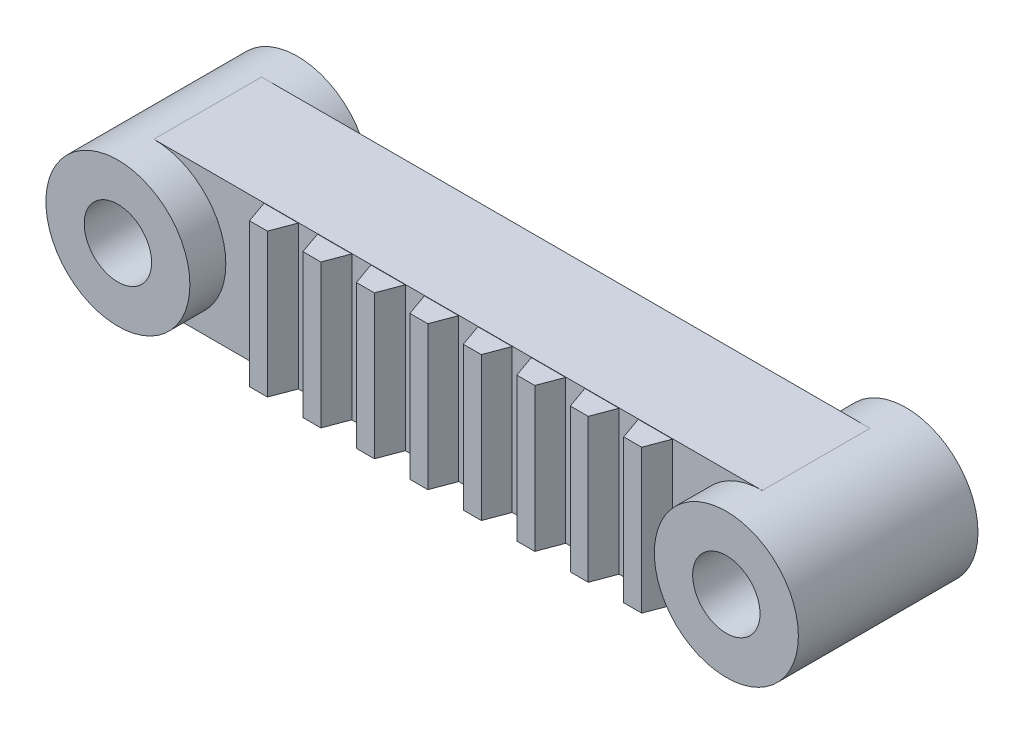
SolidWorks part; units mm, degrees
material "Galvanized Steel"
ref_plane "Front Plane" through (0, 0, 0) normal (0, 0, 1) x (1, 0, 0)
ref_plane "Top Plane" through (0, 0, 0) normal (0, 1, 0) x (1, 0, 0)
ref_plane "Right Plane" through (0, 0, 0) normal (1, 0, 0) x (0, 0, -1)
sketch "Sketch3" plane through (0, 0, 0) normal (0, 0, 1) x (1, 0, 0)
  line L0 (-140288.9448, 14884.8898) -> (-72550.8644, 14884.8898)
  line L1 (-140288.9448, -1150.8743) -> (-72550.8644, -1150.8743)
  circle A2 centre (-140288.9448, 6867.0078) radius 8017.8821
  circle A3 centre (-72550.8644, 6867.0078) radius 8017.8821
  circle A4 centre (-140288.9448, 6867.0078) radius 3750
  circle A5 centre (-72550.8644, 6867.0078) radius 3750
extrude "Boss-Extrude1" add sketch "Sketch3" along normal blind 20000 contours A5 | A3 | A2 | A4
sketch "Sketch4" plane through (0, 0, 0) normal (0, 0, 1) x (1, 0, 0)
  line L0 (-72550.8644, 14884.8898) -> (-140288.9448, 14884.8898)
  line L1 (-72550.8644, -1150.8743) -> (-140288.9448, -1150.8743)
  arc A0 (-72550.8644, 14884.8898) -> (-72550.8644, -1150.8743) centre (-72550.8644, 6867.0078) ccw
  arc A1 (-72550.8644, 14884.8898) -> (-72550.8644, -1150.8743) centre (-72550.8644, 6867.0078) ccw
  arc A2 (-72550.8644, 14884.8898) -> (-72550.8644, -1150.8743) centre (-72550.8644, 6867.0078) ccw
  arc A3 (-140288.9448, 14884.8898) -> (-140288.9448, -1150.8743) centre (-140288.9448, 6867.0078) cw
extrude "Boss-Extrude2" add sketch "Sketch4" along normal blind 12000 from offset 4000 contours L0 A3 L1 A0
sketch "Sketch6" plane through (0, -1150.8743, 0) normal (0, -1, 0) x (1, 0, 0)
  line L0 (-86353.0627, 16000) -> (-85472.8775, 18500)
  line L1 (-72550.8644, 16000) -> (-140288.9448, 16000) construction
  line L2 (-85472.8775, 18500) -> (-83472.8775, 18500)
  line L3 (-83472.8775, 18500) -> (-82532.9823, 16000)
  line L4 (-82532.9823, 16000) -> (-86353.0627, 16000)
  line L7 (-64532.9823, 0) -> (-64532.9823, 20000) construction
  line L10 (-92305.4703, 16000) -> (-91425.2851, 18500)
  line L11 (-91425.2851, 18500) -> (-89425.2851, 18500)
  line L12 (-89425.2851, 18500) -> (-88485.39, 16000)
  line L13 (-88485.39, 16000) -> (-92305.4703, 16000)
  line L14 (-98257.8779, 16000) -> (-97377.6928, 18500)
  line L15 (-97377.6928, 18500) -> (-95377.6928, 18500)
  line L16 (-95377.6928, 18500) -> (-94437.7976, 16000)
  line L17 (-94437.7976, 16000) -> (-98257.8779, 16000)
  line L18 (-104210.2856, 16000) -> (-103330.1004, 18500)
  line L19 (-103330.1004, 18500) -> (-101330.1004, 18500)
  line L20 (-101330.1004, 18500) -> (-100390.2052, 16000)
  line L21 (-100390.2052, 16000) -> (-104210.2856, 16000)
  line L22 (-110162.6932, 16000) -> (-109282.508, 18500)
  line L23 (-109282.508, 18500) -> (-107282.508, 18500)
  line L24 (-107282.508, 18500) -> (-106342.6128, 16000)
  line L25 (-106342.6128, 16000) -> (-110162.6932, 16000)
  line L26 (-116115.1008, 16000) -> (-115234.9157, 18500)
  line L27 (-115234.9157, 18500) -> (-113234.9157, 18500)
  line L28 (-113234.9157, 18500) -> (-112295.0205, 16000)
  line L29 (-112295.0205, 16000) -> (-116115.1008, 16000)
  line L30 (-122067.5084, 16000) -> (-121187.3233, 18500)
  line L31 (-121187.3233, 18500) -> (-119187.3233, 18500)
  line L32 (-119187.3233, 18500) -> (-118247.4281, 16000)
  line L33 (-118247.4281, 16000) -> (-122067.5084, 16000)
  line L34 (-128019.9161, 16000) -> (-127139.7309, 18500)
  line L35 (-127139.7309, 18500) -> (-125139.7309, 18500)
  line L36 (-125139.7309, 18500) -> (-124199.8357, 16000)
  line L37 (-124199.8357, 16000) -> (-128019.9161, 16000)
  line L103 (-137044.5462, 18500) -> (-136104.651, 16000) [skipped]
  line L104 (-136104.651, 16000) -> (-139924.7313, 16000) [skipped]
  line L105 (-139924.7313, 16000) -> (-139044.5462, 18500) [skipped]
  line L106 (-139044.5462, 18500) -> (-137044.5462, 18500) [skipped]
  line L107 (-142057.0586, 16000) -> (-145877.1389, 16000) [skipped]
  line L108 (-142996.9538, 18500) -> (-142057.0586, 16000) [skipped]
  line L109 (-144996.9538, 18500) -> (-142996.9538, 18500) [skipped]
  line L110 (-145877.1389, 16000) -> (-144996.9538, 18500) [skipped]
  line L111 (-151829.5466, 16000) -> (-150949.3614, 18500) [skipped]
  line L112 (-150949.3614, 18500) -> (-148949.3614, 18500) [skipped]
  line L113 (-148949.3614, 18500) -> (-148009.4662, 16000) [skipped]
  line L114 (-157781.9542, 16000) -> (-156901.769, 18500) [skipped]
  line L115 (-156901.769, 18500) -> (-154901.769, 18500) [skipped]
  line L116 (-154901.769, 18500) -> (-153961.8739, 16000) [skipped]
  line L117 (-153961.8739, 16000) -> (-157781.9542, 16000) [skipped]
  line L118 (-163734.3618, 16000) -> (-162854.1767, 18500) [skipped]
  line L119 (-162854.1767, 18500) -> (-160854.1767, 18500) [skipped]
  line L120 (-160854.1767, 18500) -> (-159914.2815, 16000) [skipped]
  line L121 (-159914.2815, 16000) -> (-163734.3618, 16000) [skipped]
  line L122 (-169686.7695, 16000) -> (-168806.5843, 18500) [skipped]
  line L123 (-168806.5843, 18500) -> (-166806.5843, 18500) [skipped]
  line L124 (-166806.5843, 18500) -> (-165866.6891, 16000) [skipped]
  line L125 (-165866.6891, 16000) -> (-169686.7695, 16000) [skipped]
  line L126 (-175639.1771, 16000) -> (-174758.9919, 18500) [skipped]
  line L127 (-172758.9919, 18500) -> (-171819.0967, 16000) [skipped]
  line L128 (-171819.0967, 16000) -> (-175639.1771, 16000) [skipped]
  line L129 (-181591.5847, 16000) -> (-180711.3996, 18500) [skipped]
  line L130 (-178711.3996, 18500) -> (-177771.5044, 16000) [skipped]
  line L131 (-177771.5044, 16000) -> (-181591.5847, 16000) [skipped]
  line L132 (-184663.8072, 18500) -> (-183723.912, 16000) [skipped]
  line L133 (-183723.912, 16000) -> (-187543.9923, 16000) [skipped]
  line L134 (-148009.4662, 16000) -> (-151829.5466, 16000) [skipped]
  line L135 (-174758.9919, 18500) -> (-172758.9919, 18500) [skipped]
  line L136 (-180711.3996, 18500) -> (-178711.3996, 18500) [skipped]
  line L137 (-187543.9923, 16000) -> (-186663.8072, 18500) [skipped]
  line L138 (-186663.8072, 18500) -> (-184663.8072, 18500) [skipped]
  line L139 (-193496.4, 16000) -> (-192616.2148, 18500) [skipped]
  line L140 (-192616.2148, 18500) -> (-190616.2148, 18500) [skipped]
  line L141 (-190616.2148, 18500) -> (-189676.3196, 16000) [skipped]
  line L142 (-189676.3196, 16000) -> (-193496.4, 16000) [skipped]
  line L143 (-199448.8076, 16000) -> (-198568.6224, 18500) [skipped]
  line L144 (-198568.6224, 18500) -> (-196568.6224, 18500) [skipped]
  line L145 (-196568.6224, 18500) -> (-195628.7273, 16000) [skipped]
  line L146 (-195628.7273, 16000) -> (-199448.8076, 16000) [skipped]
  line L147 (-205401.2152, 16000) -> (-204521.0301, 18500) [skipped]
  line L148 (-204521.0301, 18500) -> (-202521.0301, 18500) [skipped]
  line L149 (-202521.0301, 18500) -> (-201581.1349, 16000) [skipped]
  line L150 (-201581.1349, 16000) -> (-205401.2152, 16000) [skipped]
  line L151 (-211353.6229, 16000) -> (-210473.4377, 18500) [skipped]
  line L152 (-210473.4377, 18500) -> (-208473.4377, 18500) [skipped]
  line L153 (-208473.4377, 18500) -> (-207533.5425, 16000) [skipped]
  line L154 (-207533.5425, 16000) -> (-211353.6229, 16000) [skipped]
  line L155 (-217306.0305, 16000) -> (-216425.8453, 18500) [skipped]
  line L156 (-216425.8453, 18500) -> (-214425.8453, 18500) [skipped]
  line L157 (-214425.8453, 18500) -> (-213485.9501, 16000) [skipped]
  line L158 (-213485.9501, 16000) -> (-217306.0305, 16000) [skipped]
  line L159 (-223258.4381, 16000) -> (-222378.253, 18500) [skipped]
  line L160 (-222378.253, 18500) -> (-220378.253, 18500) [skipped]
  line L161 (-220378.253, 18500) -> (-219438.3578, 16000) [skipped]
  line L162 (-219438.3578, 16000) -> (-223258.4381, 16000) [skipped]
  line L163 (-133972.3237, 16000) -> (-133092.1385, 18500) [skipped]
  line L164 (-133092.1385, 18500) -> (-131092.1385, 18500) [skipped]
  line L165 (-131092.1385, 18500) -> (-130152.2434, 16000) [skipped]
  line L166 (-130152.2434, 16000) -> (-133972.3237, 16000) [skipped]
  point P7 (-167806.5843, 18500)
  point P8 (-167806.5843, 18500)
  point P9 (-84472.8775, 18500)
  point P11 (-161854.1767, 18500)
  point P12 (-161854.1767, 18500)
  point P13 (-84472.8775, 18500)
  point P15 (-155901.769, 18500)
  point P16 (-155901.769, 18500)
  point P17 (-149949.3614, 18500)
  point P18 (-149949.3614, 18500)
  point P23 (-90425.2851, 18500)
  point P24 (-90425.2851, 18500)
  point P29 (-96377.6928, 18500)
  point P30 (-96377.6928, 18500)
  point P35 (-102330.1004, 18500)
  point P36 (-102330.1004, 18500)
  point P41 (-108282.508, 18500)
  point P42 (-108282.508, 18500)
  point P47 (-114234.9157, 18500)
  point P48 (-114234.9157, 18500)
  point P53 (-120187.3233, 18500)
  point P54 (-120187.3233, 18500)
  point P59 (-126139.7309, 18500)
  point P60 (-126139.7309, 18500)
  point P65 (-132092.1385, 18500)
  point P66 (-132092.1385, 18500)
  point P67 (-221378.253, 18500)
  point P68 (-221378.253, 18500)
  point P69 (-215425.8453, 18500)
  point P70 (-215425.8453, 18500)
  point P71 (-138044.5462, 18500)
  point P72 (-138044.5462, 18500)
  point P73 (-209473.4377, 18500)
  point P74 (-209473.4377, 18500)
  point P75 (-203521.0301, 18500)
  point P76 (-203521.0301, 18500)
  point P77 (-143996.9538, 18500)
  point P78 (-143996.9538, 18500)
  point P79 (-197568.6224, 18500)
  point P80 (-197568.6224, 18500)
  point P81 (-191616.2148, 18500)
  point P82 (-191616.2148, 18500)
  point P83 (-185663.8072, 18500)
  point P84 (-185663.8072, 18500)
  point P85 (-179711.3996, 18500)
  point P86 (-179711.3996, 18500)
  point P87 (-173758.9919, 18500)
  point P88 (-173758.9919, 18500)
  line M238 (-72550.8644, 16000) -> (-140288.9448, 16000)
  dimension "D1" = 2000
  dimension "D2" = 2500
  dimension "D3" = 2500
  dimension "D4" = 40
  dimension "D5" = 18000
  dimension "D6" = 24
extrude "Boss-Extrude3" add sketch "Sketch6" against normal blind 16000 contours L32 L31 L30 M238 | L28 L27 L26 M238 | L24 L23 L22 M238 | L20 L19 L18 M238 | L16 L15 L14 M238 | L12 L11 L10 M238 | L3 L2 L0 M238 | L34 L35 L36 L37
